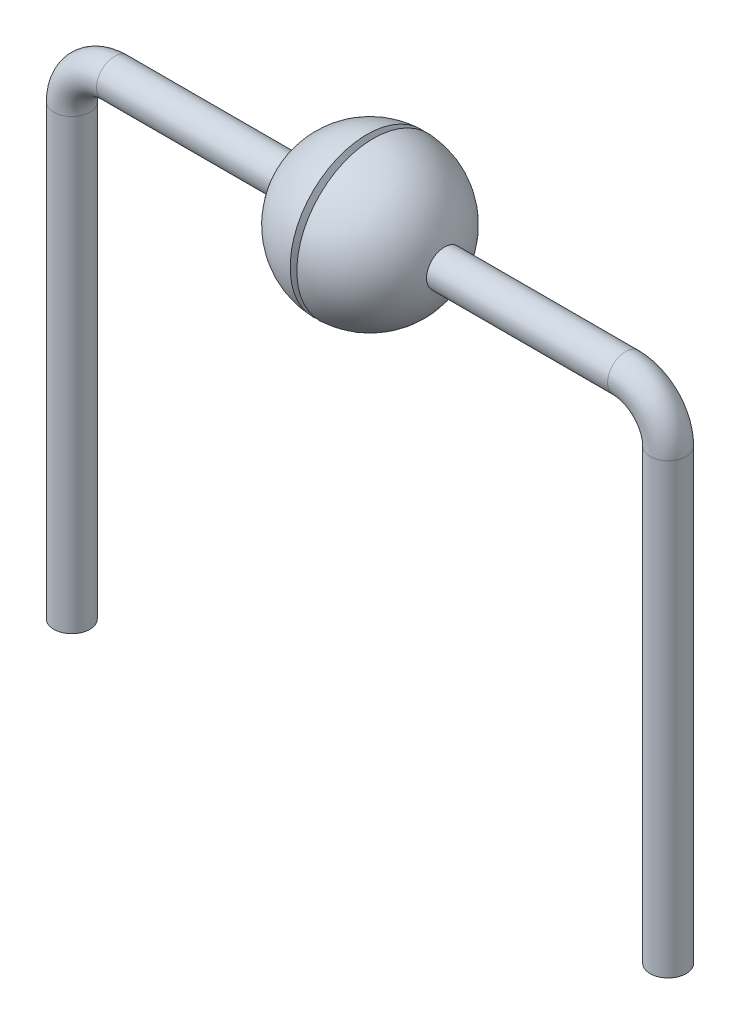
SolidWorks part; units mm, degrees
ref_plane "Спереди" through (0, 0, 0) normal (0, 0, 1) x (1, 0, 0)
ref_plane "Сверху" through (0, 0, 0) normal (0, 1, 0) x (1, 0, 0)
ref_plane "Справа" through (0, 0, 0) normal (1, 0, 0) x (0, 0, -1)
sketch "Эскиз1" plane through (0, 0, 0) normal (0, 1, 0) x (1, 0, 0)
  line L0 (-29.7512, 0) -> (31.712, 0) construction
  line L1 (-1.7496, 0.4231) -> (-1.7496, 0)
  line L2 (-1.7496, 0) -> (1.7496, 0)
  line L4 (1.7496, 0) -> (1.7496, 0.4231)
  line L5 (-0.0758, 1.7984) -> (0, 1.6459)
  line L6 (0, 1.6459) -> (0.081, 1.7982)
  line L7 (0, 1.6459) -> (0, -0.8803) construction
  arc A0 (0.081, 1.7982) -> (1.7496, 0.4231) centre (0, 0) cw
  arc A1 (-1.7496, 0.4231) -> (-0.0758, 1.7984) centre (0, 0) cw
revolve "Повернуть2" add sketch "Эскиз1" angle 360 about L0
sketch "Эскиз2" plane through (0, 0, 0) normal (0, 0, 1) x (1, 0, 0)
  line L0 (0, 0) -> (-6, 0)
  line L1 (-7, -1) -> (-7, -11.5149)
  arc A1 (-6, 0) -> (-7, -1) centre (-6, -1) ccw
  dimension "D2" = 7
sketch "Эскиз3" plane through (-1.7496, 0, 0) normal (-1, 0, 0) x (0, 0, 1)
  circle A0 centre (0, 0) radius 0.4231
sweep "По траектории1" add profiles "Эскиз3" path "Эскиз2"
mirror "Зеркальное отражение1" about plane through (0, 0, 0) normal (1, 0, 0) of "По траектории1"
